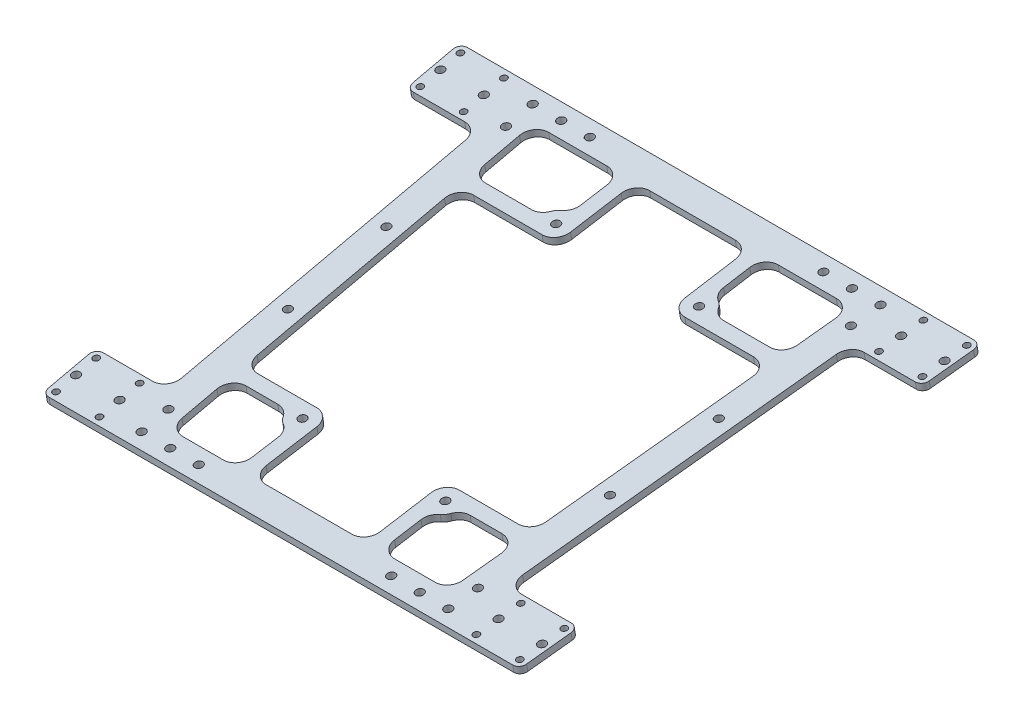
SolidWorks part; units mm, degrees
material "6061-T6 (SS)"
ref_plane "Front Plane" through (0, 0, 0) normal (0, 0, 1) x (1, 0, 0)
ref_plane "Top Plane" through (0, 0, 0) normal (0, 1, 0) x (1, 0, 0)
ref_plane "Right Plane" through (0, 0, 0) normal (1, 0, 0) x (0, 0, -1)
sketch "Sketch1" plane through (0, 638.2734, 104.8986) normal (0, 0.9868, 0.1622) x (1, 0, 0)
  line L1 (212.2764, -1251.6475) -> (231.8308, -855.311) construction
  line L4 (212.5742, -1245.6104) -> (214.454, -1207.5104)
  line L8 (0, -1251.6475) -> (212.2764, -1251.6475) construction
  line L9 (0, -1429.829) -> (0, -657.6068) construction
  line L10 (231.8308, -855.311) -> (0, -855.311) construction
  line L11 (0, -1251.6475) -> (206.2319, -1251.6475)
  line L12 (0, -1251.6475) -> (0, -855.311)
  line L13 (225.1598, -855.311) -> (0, -855.311)
  line L14 (150.9615, -1200.8475) -> (214.7827, -1200.8475) construction
  line L15 (150.9615, -1200.8475) -> (165.5032, -906.111) construction
  line L16 (165.5032, -906.111) -> (229.3245, -906.111) construction
  line L17 (150.9615, -1200.8475) -> (208.1117, -1200.8475)
  line L18 (150.9615, -1200.8475) -> (165.5032, -906.111)
  line L19 (165.5032, -906.111) -> (223.28, -906.111)
  line L20 (229.6223, -900.0739) -> (231.5021, -861.9739)
  line L21 (141.3255, -880.711) -> (0, -880.711) construction
  line L22 (124.2774, -1226.2475) -> (141.3255, -880.711) construction
  line L23 (0, -1226.2475) -> (124.2774, -1226.2475) construction
  line L24 (141.3255, -880.711) -> (0, -880.711)
  line L25 (124.2774, -1226.2475) -> (141.3255, -880.711)
  line L26 (0, -1226.2475) -> (124.2774, -1226.2475)
  arc A0 (225.1598, -855.311) -> (231.5021, -861.9739) centre (225.1598, -861.661) cw
  arc A1 (223.28, -906.111) -> (229.6223, -900.0739) centre (223.28, -899.761) ccw
  arc A2 (212.5742, -1245.6104) -> (206.2319, -1251.6475) centre (206.2319, -1245.2975) cw
  arc A3 (208.1117, -1200.8475) -> (214.454, -1207.5104) centre (208.1117, -1207.1975) cw
  circle A5 centre (206.2319, -1245.2975) radius 6.35 construction
extrude "Boss-Extrude1" add sketch "Sketch1" along normal up to vertex (25.527 mm away) from vertex at 19.177 contours A3 L17 L18 L19 A1 L20 A0 L13 L12 L24 L25 L26 L11 A2 L4
sketch "Sketch2" plane through (0, 638.2734, 104.8986) normal (0, 0.9868, 0.1622) x (1, 0, 0)
  line L0 (124.2774, -1226.2475) -> (141.3255, -880.711) construction
  line L1 (0, -1226.2475) -> (124.2774, -1226.2475) construction
  line L2 (63.5, -1155.0792) -> (127.7887, -1155.0792) construction
  line L3 (50.8, -1167.7792) -> (50.8, -1226.2475) construction
  line L4 (124.2774, -1226.2475) -> (127.7887, -1155.0792)
  line L5 (50.8, -1226.2475) -> (124.2774, -1226.2475)
  line L6 (63.5, -1155.0792) -> (127.7887, -1155.0792)
  line L7 (50.8, -1167.7792) -> (50.8, -1226.2475)
  line L8 (141.3255, -880.711) -> (0, -880.711) construction
  line L9 (63.5, -951.8792) -> (137.8142, -951.8792) construction
  line L10 (50.8, -939.1792) -> (50.8, -880.711) construction
  line L11 (124.2774, -1226.2475) -> (127.7887, -1155.0792)
  line L12 (141.3255, -880.711) -> (50.8, -880.711)
  line L13 (63.5, -951.8792) -> (137.8142, -951.8792)
  line L14 (50.8, -939.1792) -> (50.8, -880.711)
  line L15 (137.8142, -951.8792) -> (141.3255, -880.711)
  circle A0 centre (63.5, -1167.7792) radius 12.7 construction
  arc A1 (63.5, -1155.0792) -> (50.8, -1167.7792) centre (63.5, -1167.7792) ccw
  circle A2 centre (63.5, -939.1792) radius 12.7 construction
  arc A3 (50.8, -939.1792) -> (63.5, -951.8792) centre (63.5, -939.1792) ccw
extrude "the parent of this sketch feature is technically out of order in the assembly feature tree, but im gonna choose not to care" add sketch "Sketch2" along normal up to vertex (25.527 mm away) from vertex at 19.177 contours L6 A1 L7 L5 L4 | L14 A3 L13 L15 L12
hole_wizard "1/4 Clearance Hole1" positions "Sketch3" profile "Sketch4" hole size "1/4" standard "ANSI Inch" end condition through all
sketch "Sketch3" plane through (0, 663.4625, 109.0384) normal (0, 0.9868, 0.1622) x (1, 0, 0)
  point P0 (63.5, -1167.7792)
  point P9 (63.5, -939.1792)
sketch "Sketch4" plane through (63.5, 474.0814, 1261.3592) normal (1, 0, 0) x (0, -0.1622, 0.9868)
  line L0 (0, 0) -> (0, 69.7738)
  line L1 (0, 69.7738) -> (3.5712, 69.7738)
  line L2 (3.5712, 69.7738) -> (3.5712, 0)
  line L5 (3.5712, 0) -> (0, 0)
  line L11 (0, -6.35) -> (0, 107.95) construction
  dimension "Thru Hole Dia." = 7.1425
  dimension "Thru Hole Depth" = 69.7738
hole_wizard "#10 Clearance Hole1" positions "Sketch5" profile "Sketch6" hole size "#10" standard "ANSI Inch" end condition through all
sketch "Sketch5" plane through (0, 663.4625, 109.0384) normal (0, 0.9868, 0.1622) x (1, 0, 0)
  point P0 (167.577, -1245.2975)
  point P3 (169.4567, -1207.1975)
  point P6 (208.1117, -1207.1975)
  point P9 (206.2319, -1245.2975)
sketch "Sketch6" plane through (167.577, 461.5101, 1337.8512) normal (1, 0, 0) x (0, -0.1622, 0.9868)
  line L0 (0, 0) -> (0, 69.7738)
  line L1 (0, 69.7738) -> (2.8067, 69.7738)
  line L2 (2.8067, 69.7738) -> (2.8067, 0)
  line L5 (2.8067, 0) -> (0, 0)
  line L11 (0, -6.35) -> (0, 107.95) construction
  dimension "Thru Hole Dia." = 5.6134
  dimension "Thru Hole Depth" = 69.7738
hole_wizard "1/4 Clearance Hole2" positions "Sketch7" profile "Sketch8" hole size "1/4" standard "ANSI Inch" end condition through all
sketch "Sketch7" plane through (0, 663.4625, 109.0384) normal (0, 0.9868, 0.1622) x (1, 0, 0)
  point P4 (207.1718, -1226.2475)
  point P9 (168.5169, -1226.2475)
sketch "Sketch8" plane through (207.1718, 464.5995, 1319.0534) normal (1, 0, 0) x (0, -0.1622, 0.9868)
  line L0 (0, 0) -> (0, 69.7738)
  line L1 (0, 69.7738) -> (3.5712, 69.7738)
  line L2 (3.5712, 69.7738) -> (3.5712, 0)
  line L5 (3.5712, 0) -> (0, 0)
  line L11 (0, -6.35) -> (0, 107.95) construction
  dimension "Thru Hole Dia." = 7.1425
  dimension "Thru Hole Depth" = 69.7738
hole_wizard "1/4 Clearance Hole3" positions "Sketch9" profile "Sketch10" hole size "1/4" standard "ANSI Inch"
sketch "Sketch9" plane through (0, 663.4625, 109.0384) normal (0, 0.9868, 0.1622) x (1, 0, 0)
  point P0 (110.9662, -1238.9475)
  point P3 (85.5662, -1238.9475)
  point P6 (136.3663, -1238.9475)
  point P9 (137.6179, -1213.5783)
  point P20 (103.8676, -868.011)
  point P22 (129.2676, -868.011)
  point P24 (154.6676, -868.011)
  point P26 (153.4159, -893.3801)
  point P28 (143.2132, -1100.1711)
  point P30 (147.8206, -1006.7873)
sketch "Sketch10" plane through (110.9662, 462.5399, 1331.5853) normal (1, 0, 0) x (0, -0.1622, 0.9868)
  line L0 (0, 0) -> (0, 71.9958)
  line L1 (0, 71.9958) -> (3.5712, 69.85)
  line L2 (3.5712, 69.85) -> (3.5712, 0)
  line L5 (3.5712, 0) -> (0, 0)
  line L10 (0, 71.9958) -> (-3.5712, 69.85) construction
  line L11 (0, -6.35) -> (0, 107.95) construction
  dimension "Hole Dia." = 7.1425
  dimension "Hole Depth" = 69.85
  dimension "Drill Angle" = 118
pattern_linear "LPattern1" count 2 spacing 345.9568 along (0.0493, 0.162, -0.9856) of "#10 Clearance Hole1", "1/4 Clearance Hole2"
fillet "Fillet1" radius 12.7 6 edges at (150.9615, 465.5857, 1293.4748) (165.5032, 513.3837, 1002.6399) (50.8, 461.4665, 1318.5385) (127.7887, 473.008, 1248.3124) (50.8, 517.5029, 977.5761) (137.8142, 505.9614, 1047.8022)
sketch "Sketch11" plane through (0, 663.4625, 109.0384) normal (0, 0.9868, 0.1622) x (1, 0, 0)
  line L0 (38.1, -880.711) -> (0, -880.711) construction
  line L1 (141.3255, -880.711) -> (0, -880.711)
  line L2 (128.3844, -1143.0051) -> (137.1567, -965.2051) construction
  line L3 (124.2774, -1226.2475) -> (141.3255, -880.711)
  line L4 (63.5, -880.711) -> (63.5, -926.4792)
  line L5 (76.2, -939.1792) -> (138.4408, -939.1792)
  line L6 (63.5, -951.8792) -> (124.4722, -951.8792) construction
  line L7 (50.8, -939.1792) -> (50.8, -893.411) construction
  line L8 (0, -1226.2475) -> (38.1, -1226.2475) construction
  line L9 (0, -1226.2475) -> (124.2774, -1226.2475)
  line L10 (63.5, -1180.4792) -> (63.5, -1226.2475)
  line L11 (50.8, -1167.7792) -> (50.8, -1213.5475) construction
  line L12 (76.2, -1167.7792) -> (127.1621, -1167.7792)
  line L13 (63.5, -1155.0792) -> (115.6998, -1155.0792) construction
  circle A0 centre (63.5, -939.1792) radius 12.7
  arc A1 (50.8, -939.1792) -> (63.5, -951.8792) centre (63.5, -939.1792) ccw construction
  circle A2 centre (63.5, -1167.7792) radius 12.7
  arc A3 (63.5, -1155.0792) -> (50.8, -1167.7792) centre (63.5, -1167.7792) ccw construction
  dimension "D1" = 12.7
  dimension "D2" = 12.7
  dimension "D3" = 12.7
  dimension "D4" = 12.7
extrude "Cut-Extrude1" cut sketch "Sketch11" against normal through all both and the other way through all contours A2 L10 L9 L3 L12 | A0 L5 L3 L1 L4
fillet "Fillet2" radius 12.7 10 edges at (63.5, 510.0805, 1022.7385) (141.3255, 517.5029, 977.5761) (138.4408, 508.0209, 1035.2704) (76.2, 508.0209, 1035.2704) (63.5, 517.5029, 977.5761) (127.1621, 470.9484, 1260.8443) (124.2774, 461.4665, 1318.5385) (63.5, 461.4665, 1318.5385) (63.5, 468.8889, 1273.3762) (76.2, 470.9484, 1260.8443)
mirror "Mirror1" about plane through (0, 0, 0) normal (1, 0, 0) of bodies 109 101
equation "\"D2@Sketch11\"=\"D1@Sketch11\""
